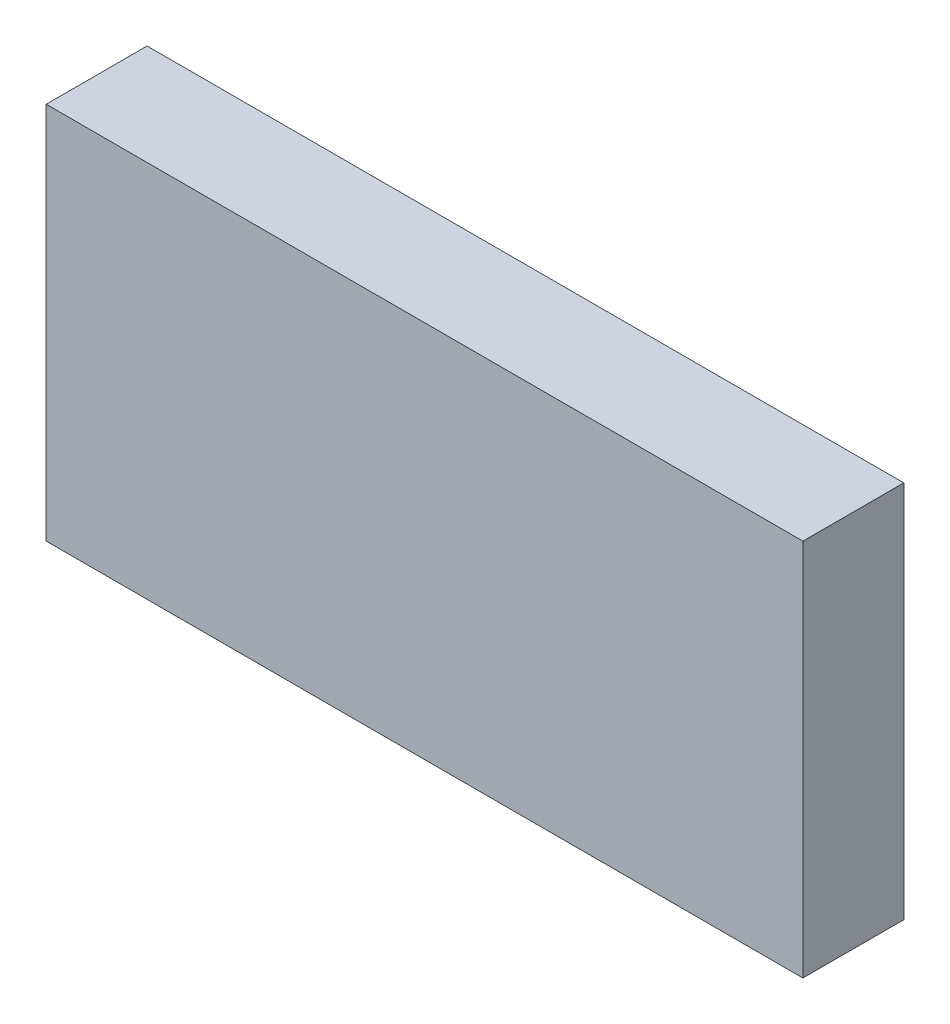
SolidWorks part; units mm, degrees
ref_plane "前视基准面" through (0, 0, 0) normal (0, 0, 1) x (1, 0, 0)
ref_plane "上视基准面" through (0, 0, 0) normal (0, 1, 0) x (1, 0, 0)
ref_plane "右视基准面" through (0, 0, 0) normal (1, 0, 0) x (0, 0, -1)
other "Configuration Table"
sketch "草图8" plane through (0, 0, 0) normal (0, 0, 1) x (1, 0, 0)
  line L0 (0, 0) -> (60, 0)
  line L1 (60, 0) -> (60, 30)
  line L2 (60, 30) -> (0, 30)
  line L3 (0, 30) -> (0, 0)
extrude "凸台-拉伸1" add sketch "草图8" along normal blind 8
